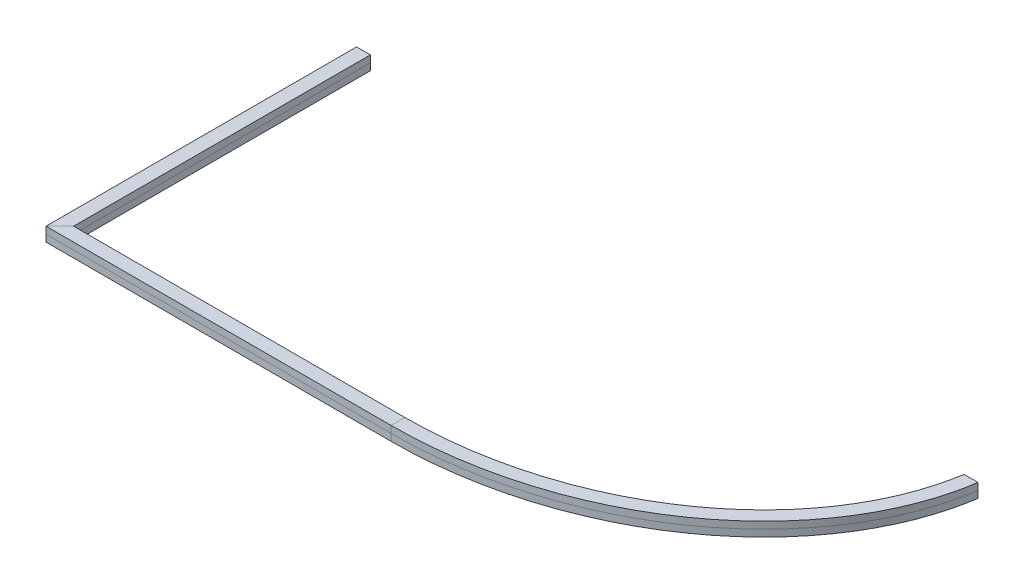
SolidWorks part; units mm, degrees
ref_plane "Front Plane" through (0, 0, 0) normal (0, 0, 1) x (1, 0, 0)
ref_plane "Top Plane" through (0, 0, 0) normal (0, 1, 0) x (1, 0, 0)
ref_plane "Right Plane" through (0, 0, 0) normal (1, 0, 0) x (0, 0, -1)
ref_plane "Plane1" through (0, 21, 0) normal (0, -1, 0) x (-1, 0, 0)
sketch "Sketch2" plane through (0, 21, 0) normal (0, -1, 0) x (-1, 0, 0)
  line L1 (79, -199) -> (-71, -199)
  line L4 (79, -79) -> (79, -199)
  ellipse E1 centre (-71, -79) end of major axis (-221, -79) minor radius 120 (-71, -199) -> (-221, -79) cw
sketch "Sketch3" plane through (0, 0, 79) normal (0, 0, 1) x (1, 0, 0)
  line L0 (-79, 18) -> (-73, 18)
  line L2 (-79, 18) -> (-79, 24)
  line L3 (-79, 24) -> (-73, 24)
  line L4 (-73, 18) -> (-73, 24)
  line L5 (-79, -4) -> (79, -4) construction
  line L6 (-79, 75) -> (-79, 23) construction
  dimension "D1" = 6
  dimension "D2" = 6
  dimension "D3" = 22
  dimension "D4" = 0
sweep "Sweep2" add profiles "Sketch3" path "Sketch2"
sketch "Sketch6" plane through (0, 0, 79) normal (0, 0, 1) x (1, 0, 0)
  line L6 (-73, 18) -> (-73, 24)
  line L7 (-79, 18) -> (-73, 18)
  line L8 (-79, 24) -> (-79, 18)
  line L9 (-73, 24) -> (-79, 24)
  line L10 (-73, 18) -> (-73, 24)
  line L11 (-79, 18) -> (-73, 18)
  line L12 (-79, 24) -> (-79, 18)
  line L13 (-73, 24) -> (-79, 24)
  dimension "D1" = 0
extrude "Boss-Extrude2" add sketch "Sketch6" against normal blind 15
sketch "Sketch13" plane through (0, 0, 92.9) normal (0, 0, 1) x (1, 0, 0)
  line L1 (206.0719, 32.2864) -> (226.1423, 32.2864)
  line L2 (206.0719, 32.2864) -> (206.0719, 12.1506)
  line L3 (206.0719, 12.1506) -> (226.1423, 12.1506)
  line L4 (226.1423, 32.2864) -> (226.1423, 12.1506)
extrude "Cut-Extrude1" cut sketch "Sketch13" against normal through all contours L4 L3 L2 L1
split "Split1" trim tools "Plane1" bodies to split 106 resulting bodies 107 108
